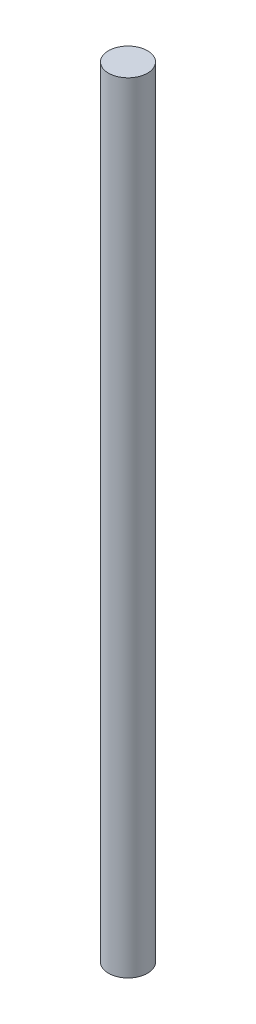
SolidWorks part; units mm, degrees
material "1060 Alloy"
ref_plane "Front Plane" through (0, 0, 0) normal (0, 0, 1) x (1, 0, 0)
ref_plane "Top Plane" through (0, 0, 0) normal (0, 1, 0) x (1, 0, 0)
ref_plane "Right Plane" through (0, 0, 0) normal (1, 0, 0) x (0, 0, -1)
sketch "Sketch1" plane through (0, 0, 0) normal (0, 1, 0) x (1, 0, 0)
  circle A0 centre (-5.3268, 0) radius 3
  dimension "D1" = 6
extrude "Boss-Extrude1" add sketch "Sketch1" along normal blind 120
